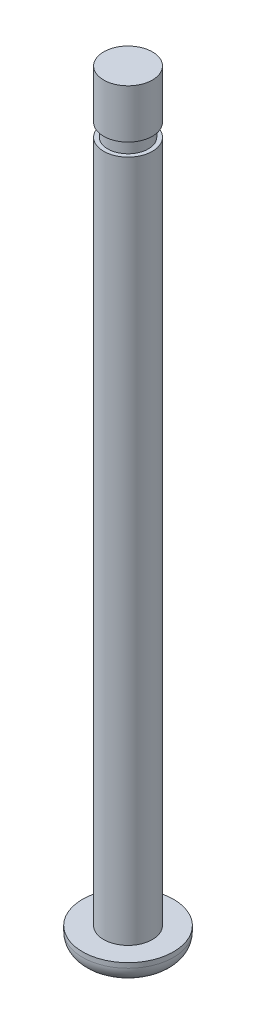
SolidWorks part; units mm, degrees
ref_plane "前视基准面" through (0, 0, 0) normal (0, 0, 1) x (1, 0, 0)
ref_plane "上视基准面" through (0, 0, 0) normal (0, 1, 0) x (1, 0, 0)
ref_plane "右视基准面" through (0, 0, 0) normal (1, 0, 0) x (0, 0, -1)
other "Configuration Table"
sketch "草图1" plane through (0, 0, 0) normal (0, 1, 0) x (1, 0, 0)
  circle A0 centre (0, 0) radius 1.5
  dimension "D1" = 3
extrude "凸台-拉伸1" add sketch "草图1" along normal blind 42
sketch "草图2" plane through (0, 42, 0) normal (0, 1, 0) x (1, 0, 0)
  circle A0 centre (0, 0) radius 1.25
  dimension "D1" = 2.5
extrude "凸台-拉伸2" add sketch "草图2" along normal blind 0.8
sketch "草图3" plane through (0, 42.8, 0) normal (0, 1, 0) x (1, 0, 0)
  circle A0 centre (0, 0) radius 1.5
  dimension "D1" = 3
extrude "凸台-拉伸3" add sketch "草图3" along normal blind 3
sketch "草图4" plane through (0, 0, 0) normal (0, -1, 0) x (1, 0, 0)
  circle A0 centre (0, 0) radius 2.8
  dimension "D1" = 5.6
extrude "凸台-拉伸4" add sketch "草图4" along normal blind 1.3
fillet "圆角1" radius 1 1 edges at (0, -1.3, -2.8)
